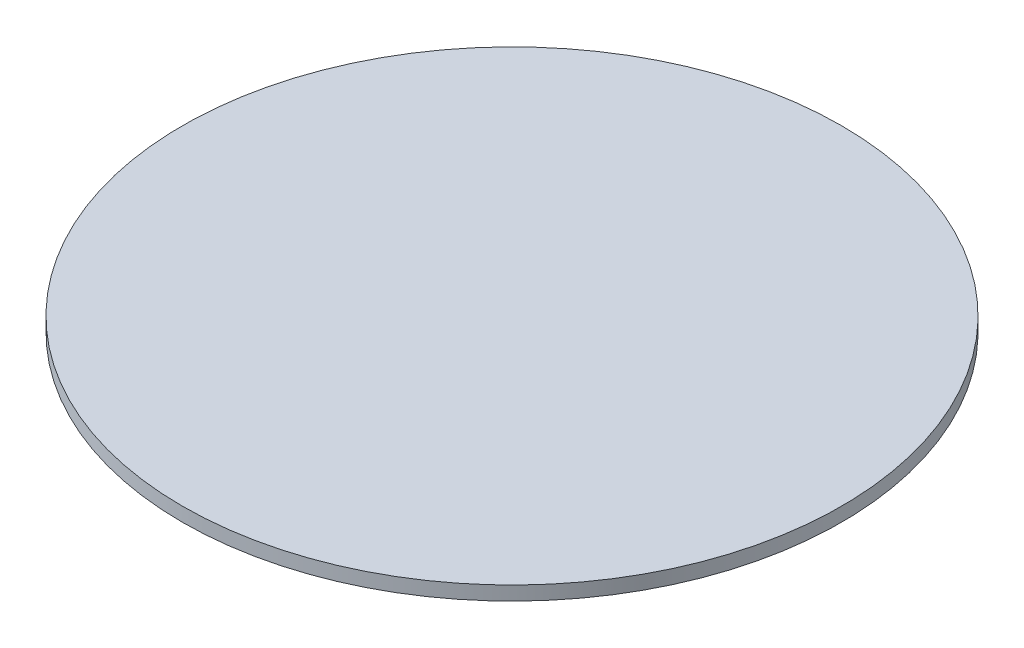
SolidWorks part; units mm, degrees
ref_plane "Front Plane" through (0, 0, 0) normal (0, 0, 1) x (1, 0, 0)
ref_plane "Top Plane" through (0, 0, 0) normal (0, 1, 0) x (1, 0, 0)
ref_plane "Right Plane" through (0, 0, 0) normal (1, 0, 0) x (0, 0, -1)
sketch "Sketch1" plane through (0, 0, 0) normal (0, 1, 0) x (1, 0, 0)
  circle A0 centre (0, 0) radius 75
  dimension "D1" = 150
extrude "Boss-Extrude1" add sketch "Sketch1" along normal blind 3.175
